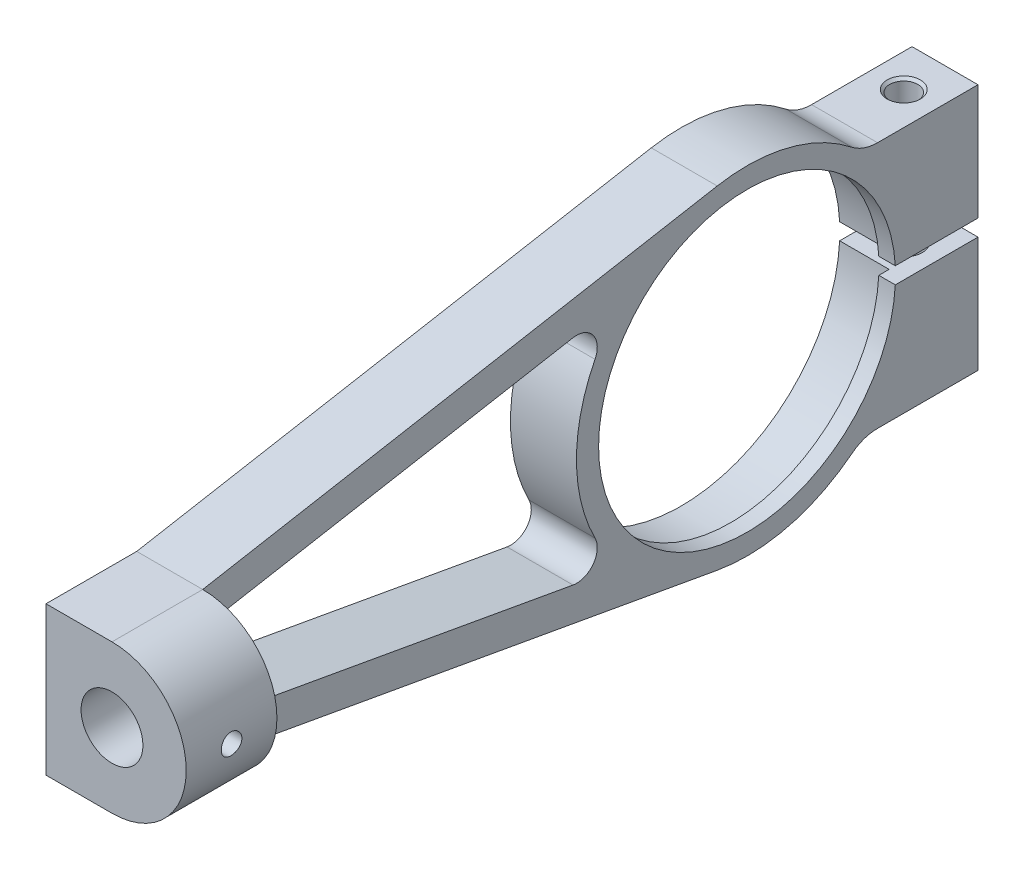
SolidWorks part; units mm, degrees
ref_plane "前视基准面" through (0, 0, 0) normal (0, 0, 1) x (1, 0, 0)
ref_plane "上视基准面" through (0, 0, 0) normal (0, 1, 0) x (1, 0, 0)
ref_plane "右视基准面" through (0, 0, 0) normal (1, 0, 0) x (0, 0, -1)
other "Configuration Table"
sketch "草图1" plane through (0, 0, 0) normal (1, 0, 0) x (0, 0, -1)
  line L0 (0, 0) -> (-235.9931, 0) construction
  line L1 (-132, -18) -> (-132, 18)
  line L2 (-132, 18) -> (-7.2316, 40.3572)
  line L3 (56, -30) -> (56, -2)
  line L4 (56, 30) -> (31.6386, 30)
  line L5 (56, -30) -> (31.6386, -30)
  line L6 (-132, -18) -> (-7.2316, -40.3572)
  line L7 (56, 2) -> (56, 30)
  line L8 (35.9444, 2) -> (56, 2)
  line L10 (35.9444, -2) -> (56, -2)
  arc A0 (25.4349, 32.1569) -> (-7.2316, 40.3572) centre (0, 0) ccw
  arc A2 (-7.2316, -40.3572) -> (25.4349, -32.1569) centre (0, 0) ccw
  arc A3 (31.6386, -30) -> (25.4349, -32.1569) centre (31.6386, -40) ccw
  arc A4 (31.6386, 30) -> (25.4349, 32.1569) centre (31.6386, 40) cw
  arc A5 (35.9444, 2) -> (36, 0) centre (0, 0) ccw
  point P11 (78.8741, 0)
  point P14 (-132, 0)
  point P15 (27.9464, -30)
  point P18 (27.9464, 30)
  point P20 (36, 0)
  dimension "D1" = 82
  dimension "D3" = 10
  dimension "D4" = 72
  dimension "D2" = 188
  dimension "D5" = 4
  dimension "D6" = 60
  dimension "D7" = 132
  dimension "D8" = 36
  dimension "D9" = 2
extrude "凸台-拉伸1" add sketch "草图1" along normal blind 16 contours L0 A5 L8 L7 L4 A4 A0 L2 L1 | A5 L0 L1 L6 A2 A3 L5 L3 L10
sketch "草图3" plane through (0, 0, 132) normal (0, 0, 1) x (1, 0, 0)
  line L0 (16, -18) -> (16, 18) construction
  line L1 (16, 18) -> (0, 18)
  line L2 (0, -18) -> (0, 18) construction
  line L3 (16, 18) -> (0, 18) construction
  line L4 (0, 18) -> (0, -18)
  line L5 (0, -18) -> (16, -18)
  arc A0 (16, -18) -> (16, 18) centre (16, 0) ccw
  circle A1 centre (16, 0) radius 7.5
  dimension "D1" = 15
extrude "凸台-拉伸2" add sketch "草图3" along normal blind 22
sketch "草图4" plane through (0, 0, 0) normal (-1, 0, 0) x (0, 0, 1)
  circle A0 centre (0, 0) radius 38.5
  dimension "D1" = 77
extrude "切除-拉伸1" cut sketch "草图4" against normal blind 12
sketch "草图5" plane through (16, 0, 0) normal (1, 0, 0) x (0, 0, -1)
  line L0 (0, 0) -> (-104.1815, 0) construction
  line L1 (-132, -9.8726) -> (-132, 9.8726)
  line L2 (-132, -18) -> (-132, 18) construction
  line L3 (-132, 7.5) -> (-132, 18) construction
  line L4 (-132, 9.8726) -> (-42.2066, 25.9626)
  line L5 (-132, 18) -> (-7.2316, 40.3572) construction
  line L6 (-132, -9.8726) -> (-42.2066, -25.9626)
  arc A0 (-36.869, 18.7723) -> (-36.869, -18.7723) centre (0, 0) ccw
  arc A1 (-42.2066, -25.9626) -> (-36.869, -18.7723) centre (-41.3247, -21.041) ccw
  arc A2 (-42.2066, 25.9626) -> (-36.869, 18.7723) centre (-41.3247, 21.041) cw
  point P14 (-132, 0)
  point P16 (-30.3838, -28.0811)
  point P19 (-30.3838, 28.0811)
  dimension "D2" = 5
  dimension "D1" = 8
extrude "切除-拉伸2" cut sketch "草图5" against normal up to surface (16 mm away) up to face at (0, 0, 15.4357)
sketch "草图6" plane through (0, 0, 0) normal (-1, 0, 0) x (0, 0, 1)
  line L0 (154, 18) -> (154, -18) construction
  circle A0 centre (143, 0) radius 2.5
  dimension "D1" = 5
  dimension "D2" = 11
extrude "切除-拉伸3" cut sketch "草图6" against normal up to surface (34 mm away)
sketch "草图7" plane through (0, -30, 0) normal (0, -1, 0) x (1, 0, 0)
  line L0 (16, -56) -> (0, -56) construction
  line L1 (16, -56) -> (16, -31.6386) construction
  circle A0 centre (8, -46) radius 4.5
  dimension "D1" = 9
  dimension "D2" = 10
  dimension "D3" = 8
extrude "切除-拉伸4" cut sketch "草图7" against normal up to surface (28 mm away) up to face at (9.3333, -2, -43.4641)
sketch "草图10" plane through (0, 30, 0) normal (0, 1, 0) x (1, 0, 0)
  point P0 (8, 46)
  point P3 (8, 46)
hole_wizard "M8 螺纹孔1" positions "草图10" profile "草图9" tap size "M8" standard "GB" end condition up to next
sketch "草图9" plane through (8, 30, -46) normal (1, 0, 0) x (0, 0, 1)
  line L0 (0, 0) -> (0, 28)
  line L1 (0, 28) -> (3.4, 28)
  line L2 (3.4, 28) -> (3.4, 0.625)
  line L3 (3.4, 0.625) -> (4.025, 0)
  line L5 (4.025, 0) -> (0, 0)
  line L6 (-3.4, 0.625) -> (-4.025, 0) construction
  line L11 (0, -6.35) -> (0, 107.95) construction
  dimension "通孔螺纹孔钻头直径" = 6.8
  dimension "通孔螺纹孔钻头深度" = 28
  dimension "近端锥形沉头孔直径" = 8.05
  dimension "近端锥形沉头孔角度" = 90
cosmetic thread "孔螺纹线1" parameters "D2"=8
cosmetic thread "孔螺纹线2" parameters "D2"=8
